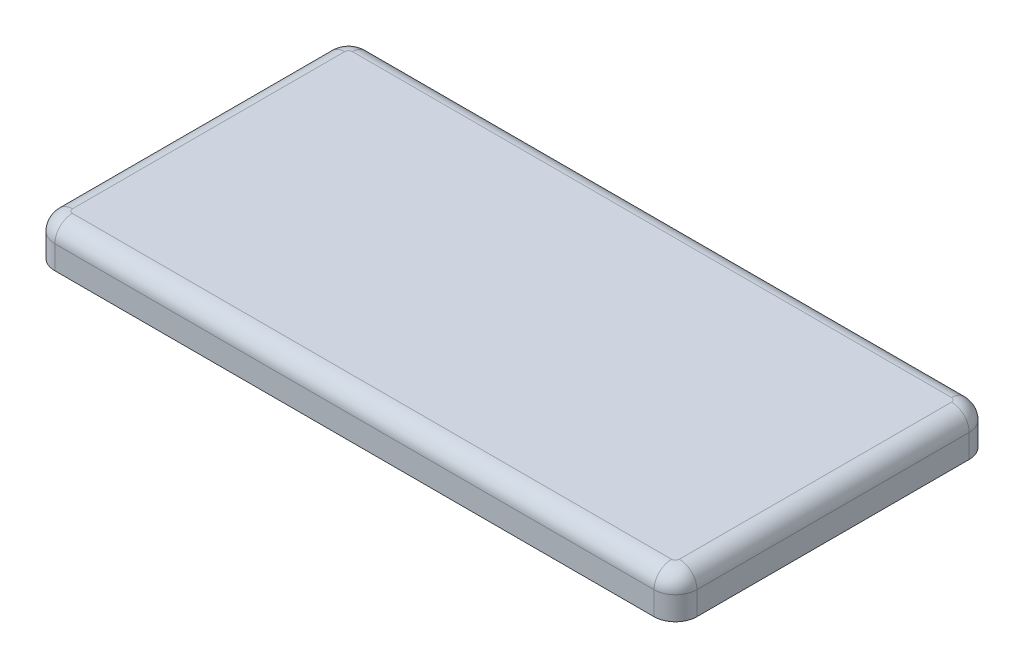
SolidWorks part; units mm, degrees
material "自定义塑料"
ref_plane "前视基准面" through (0, 0, 0) normal (0, 0, 1) x (1, 0, 0)
ref_plane "上视基准面" through (0, 0, 0) normal (0, 1, 0) x (1, 0, 0)
ref_plane "右视基准面" through (0, 0, 0) normal (1, 0, 0) x (0, 0, -1)
sketch "草图1" plane through (0, 0, 0) normal (0, 1, 0) x (1, 0, 0)
  line L1 (-30.7, 16.15) -> (30.7, 16.15)
  line L2 (-32.9, 13.95) -> (-32.9, -13.95)
  line L3 (-30.7, -16.15) -> (30.7, -16.15)
  line L4 (32.9, 13.95) -> (32.9, -13.95)
  line L5 (-32.9, 16.15) -> (32.9, -16.15) construction
  line L6 (-32.9, -16.15) -> (32.9, 16.15) construction
  arc A0 (-32.9, -13.95) -> (-30.7, -16.15) centre (-30.7, -13.95) ccw
  arc A1 (30.7, -16.15) -> (32.9, -13.95) centre (30.7, -13.95) ccw
  arc A2 (30.7, 16.15) -> (32.9, 13.95) centre (30.7, 13.95) cw
  arc A3 (-30.7, 16.15) -> (-32.9, 13.95) centre (-30.7, 13.95) ccw
  point P0 (0, 0)
  dimension "D3" = 2.2
  dimension "D1" = 65.8
  dimension "D2" = 32.3
extrude "凸台-拉伸1" add sketch "草图1" along normal blind 4.2
fillet "圆角1" radius 1.8 8 edges at (32.2556, 4.2, 15.5056) (32.9, 4.2, 0) (32.2556, 4.2, -15.5056) (0, 4.2, -16.15) (-32.2556, 4.2, -15.5056) (-32.9, 4.2, 0) (-32.2556, 4.2, 15.5056) (0, 4.2, 16.15)
shell "抽壳1" thickness 1
